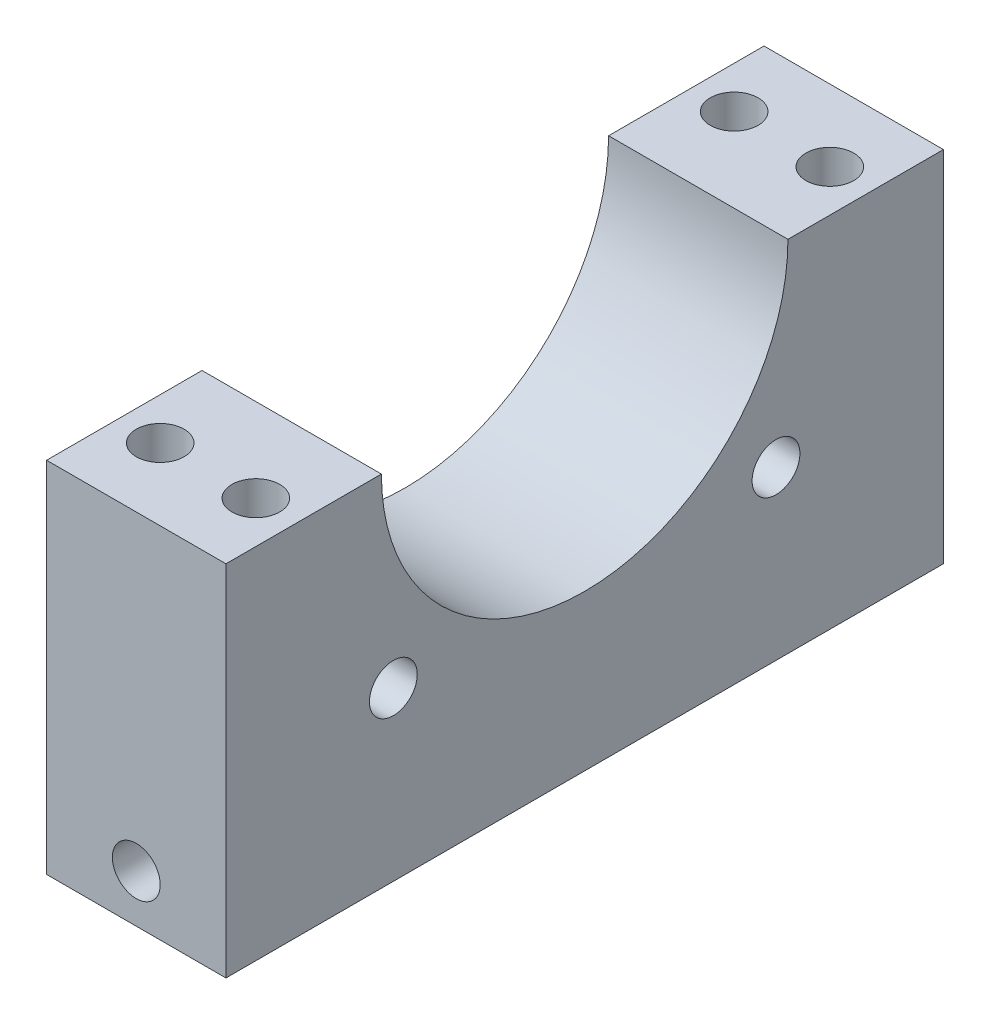
SolidWorks part; units mm, degrees
material "ABS"
ref_plane "Front Plane" through (0, 0, 0) normal (0, 0, 1) x (1, 0, 0)
ref_plane "Top Plane" through (0, 0, 0) normal (0, 1, 0) x (1, 0, 0)
ref_plane "Right Plane" through (0, 0, 0) normal (1, 0, 0) x (0, 0, -1)
other "Configuration Table"
sketch "Sketch1" plane through (0, 0, 0) normal (0, 1, 0) x (1, 0, 0)
  line L1 (7.5, -30) -> (-7.5, -30)
  line L2 (7.5, -30) -> (7.5, 30)
  line L3 (7.5, 30) -> (-7.5, 30)
  line L4 (-7.5, -30) -> (-7.5, 30)
  line L5 (7.5, -30) -> (-7.5, 30) construction
  line L6 (7.5, 30) -> (-7.5, -30) construction
  point P0 (0, 0)
  dimension "D1" = 60
  dimension "D2" = 15
extrude "Boss-Extrude1" add sketch "Sketch1" along normal blind 70
sketch "Sketch2" plane through (7.5, 0, 0) normal (1, 0, 0) x (0, 0, -1)
  line L0 (-30, 0) -> (30, 0) construction
  circle A0 centre (0, 30) radius 17
  point P9 (0, 30)
  dimension "D1" = 34
  dimension "D2" = 30
extrude "Cut-Extrude1" cut sketch "Sketch2" against normal blind 70
sketch "Sketch3" plane through (7.5, 0, 0) normal (1, 0, 0) x (0, 0, -1)
  line L0 (-30, 30) -> (30, 30)
  line L1 (30, 70) -> (30, 0) construction
  line L2 (-30, 30) -> (-30, 70)
  line L3 (-30, 70) -> (30, 70)
  line L4 (30, 70) -> (30, 30)
  point P6 (0, 30)
extrude "Cut-Extrude2" cut sketch "Sketch3" against normal blind 29
sketch "Sketch4" plane through (0, 30, 0) normal (0, 1, 0) x (1, 0, 0)
  line L0 (-7.5, 17) -> (-7.5, 30) construction
  line L1 (7.5, 17) -> (7.5, 30) construction
  line L2 (-7.5, 30) -> (7.5, 30) construction
  line L3 (-7.5, -30) -> (-7.5, -17) construction
  line L4 (7.5, -30) -> (7.5, -17) construction
  line L5 (-7.5, -30) -> (7.5, -30) construction
  circle A0 centre (-4, 24) radius 2
  circle A1 centre (4, 24) radius 2
  circle A2 centre (-4, -24) radius 2
  circle A3 centre (4, -24) radius 2
  dimension "D1" = 4
  dimension "D2" = 4
  dimension "D7" = 4
  dimension "D8" = 4
  dimension "D3" = 3.5
  dimension "D4" = 3.5
  dimension "D5" = 6
  dimension "D6" = 6
  dimension "D9" = 3.5
  dimension "D10" = 3.5
  dimension "D11" = 6
  dimension "D12" = 6
extrude "Cut-Extrude3" cut sketch "Sketch4" against normal blind 6
sketch "Sketch5" plane through (7.5, 0, 0) normal (1, 0, 0) x (0, 0, -1)
  line L1 (16, 14) -> (-16, 14) construction
  line L2 (16, 14) -> (16, 46) construction
  line L3 (16, 46) -> (-16, 46) construction
  line L4 (-16, 14) -> (-16, 46) construction
  line L5 (16, 14) -> (-16, 46) construction
  line L6 (16, 46) -> (-16, 14) construction
  circle A0 centre (-16, 14) radius 2
  circle A1 centre (16, 14) radius 2
  point P0 (0, 30)
  dimension "D2" = 4
  dimension "D3" = 4
  dimension "D1" = 32
extrude "Cut-Extrude4" cut sketch "Sketch5" against normal blind 10
sketch "Sketch6" plane through (0, 0, -30) normal (0, 0, -1) x (-1, 0, 0)
  circle A0 centre (0, 4) radius 2
  dimension "D1" = 4
extrude "Cut-Extrude5" cut sketch "Sketch6" against normal blind 14
sketch "Sketch7" plane through (0, 0, 30) normal (0, 0, 1) x (1, 0, 0)
  circle A0 centre (0, 4) radius 2
  dimension "D1" = 4
extrude "Cut-Extrude6" cut sketch "Sketch7" against normal blind 14
